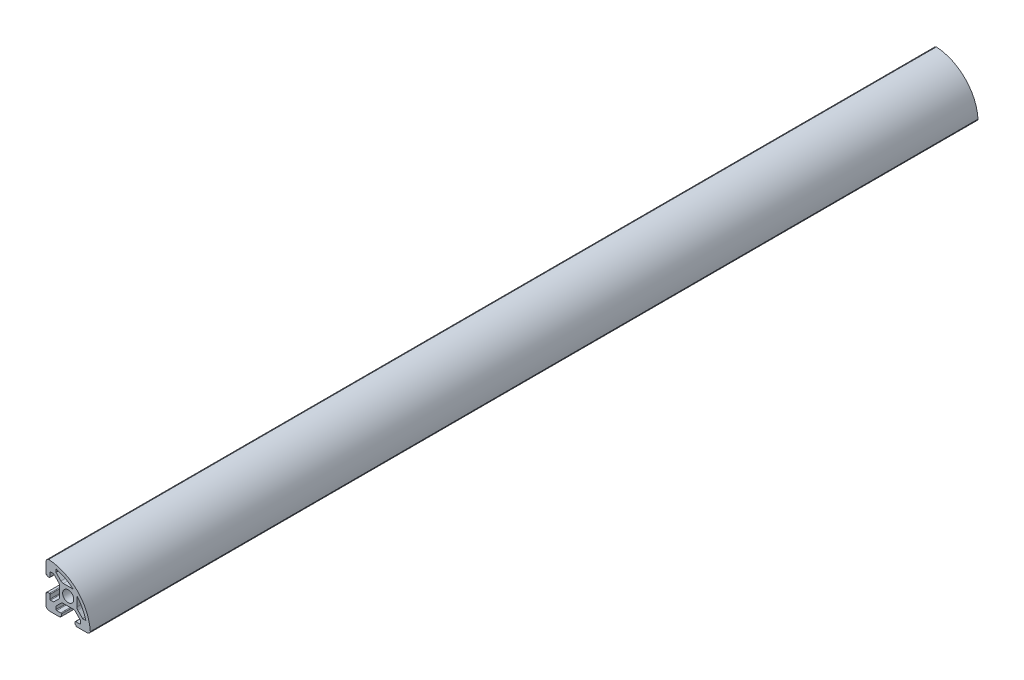
SolidWorks part; units mm, degrees
ref_plane "前视基准面" through (0, 0, 0) normal (0, 0, 1) x (1, 0, 0)
ref_plane "上视基准面" through (0, 0, 0) normal (0, 1, 0) x (1, 0, 0)
ref_plane "右视基准面" through (0, 0, 0) normal (1, 0, 0) x (0, 0, -1)
sketch "草图1" plane through (0, 0, 0) normal (0, 0, 1) x (1, 0, 0)
  line L14 (2.0848, 3.8649) -> (-2.342, 3.8649)
  line L15 (-3.4027, 4.3042) -> (-5.6233, 6.5249)
  line L16 (-5.6233, 6.5249) -> (-5.6233, 7.8649)
  line L22 (-10.1233, 8.4649) -> (-10.1233, 3.5649)
  line L23 (-10.1233, 3.5649) -> (-9.8233, 3.5649)
  line L24 (-9.6233, 3.3649) -> (-9.6233, 3.0649)
  line L25 (-9.6233, 3.0649) -> (-8.6233, 3.0649)
  line L26 (-8.3233, 3.3649) -> (-8.3233, 5.1649)
  line L27 (-8.0233, 5.4649) -> (-6.6833, 5.4649)
  line L28 (-6.6833, 5.4649) -> (-4.4627, 3.2442)
  line L29 (-4.0233, 2.1836) -> (-4.0233, -2.2538)
  line L30 (-4.4627, -3.3144) -> (-6.6833, -5.5351)
  line L31 (-6.6833, -5.5351) -> (-8.0233, -5.5351)
  line L32 (-8.3233, -5.2351) -> (-8.3233, -3.4351)
  line L33 (-8.6233, -3.1351) -> (-9.6233, -3.1351)
  line L34 (-9.6233, -3.1351) -> (-9.6233, -3.4351)
  line L35 (-9.8233, -3.6351) -> (-10.1233, -3.6351)
  line L36 (-10.1233, -3.6351) -> (-10.1233, -8.5351)
  line L37 (-8.6233, -10.0351) -> (-3.7233, -10.0351)
  line L38 (-3.7233, -10.0351) -> (-3.7233, -9.7351)
  line L39 (-3.5233, -9.5351) -> (-3.2233, -9.5351)
  line L40 (-3.2233, -9.5351) -> (-3.2233, -8.5351)
  line L41 (-3.5233, -8.2351) -> (-5.3233, -8.2351)
  line L42 (-5.6233, -7.9351) -> (-5.6233, -6.5951)
  line L43 (-5.6233, -6.5951) -> (-3.4027, -4.3744)
  line L44 (-2.342, -3.9351) -> (2.0953, -3.9351)
  line L45 (3.156, -4.3744) -> (5.3767, -6.5951)
  line L46 (5.3767, -6.5951) -> (5.3767, -7.9351)
  line L47 (5.0767, -8.2351) -> (3.2767, -8.2351)
  line L48 (2.9767, -8.5351) -> (2.9767, -9.5351)
  line L49 (2.9767, -9.5351) -> (3.2767, -9.5351)
  line L50 (3.4767, -9.7351) -> (3.4767, -10.0351)
  line L51 (3.4767, -10.0351) -> (8.3767, -10.0351)
  line L57 (7.7767, -5.5351) -> (6.4367, -5.5351)
  line L58 (6.4367, -5.5351) -> (4.216, -3.3144)
  line L59 (3.7767, -2.2538) -> (3.7767, 2.1836)
  circle A0 centre (-0.1233, -0.0351) radius 2.5
  arc A1 (7.8202, -5.5319) -> (3.7767, 2.1731) centre (-10.1233, -10.0351) ccw
  arc A2 (2.0848, 3.8649) -> (-5.6202, 7.9085) centre (-10.1233, -10.0351) ccw
  arc A9 (-3.4027, 4.3042) -> (-2.342, 3.8649) centre (-2.342, 5.3649) ccw
  arc A10 (-5.3233, 8.1649) -> (-5.6233, 7.8649) centre (-5.3233, 7.8649) ccw
  arc A13 (-8.6233, 9.9649) -> (-10.1233, 8.4649) centre (-8.6233, 8.4649) ccw
  arc A14 (-9.6233, 3.3649) -> (-9.8233, 3.5649) centre (-9.8233, 3.3649) ccw
  arc A15 (-8.6233, 3.0649) -> (-8.3233, 3.3649) centre (-8.6233, 3.3649) ccw
  arc A16 (-8.0233, 5.4649) -> (-8.3233, 5.1649) centre (-8.0233, 5.1649) ccw
  arc A17 (-4.0233, 2.1836) -> (-4.4627, 3.2442) centre (-5.5233, 2.1836) ccw
  arc A18 (-4.4627, -3.3144) -> (-4.0233, -2.2538) centre (-5.5233, -2.2538) ccw
  arc A19 (-8.3233, -5.2351) -> (-8.0233, -5.5351) centre (-8.0233, -5.2351) ccw
  arc A20 (-8.3233, -3.4351) -> (-8.6233, -3.1351) centre (-8.6233, -3.4351) ccw
  arc A21 (-9.8233, -3.6351) -> (-9.6233, -3.4351) centre (-9.8233, -3.4351) ccw
  arc A22 (-10.1233, -8.5351) -> (-8.6233, -10.0351) centre (-8.6233, -8.5351) ccw
  arc A23 (-3.5233, -9.5351) -> (-3.7233, -9.7351) centre (-3.5233, -9.7351) ccw
  arc A24 (-3.2233, -8.5351) -> (-3.5233, -8.2351) centre (-3.5233, -8.5351) ccw
  arc A25 (-5.6233, -7.9351) -> (-5.3233, -8.2351) centre (-5.3233, -7.9351) ccw
  arc A26 (-2.342, -3.9351) -> (-3.4027, -4.3744) centre (-2.342, -5.4351) ccw
  arc A27 (3.156, -4.3744) -> (2.0953, -3.9351) centre (2.0953, -5.4351) ccw
  arc A28 (5.0767, -8.2351) -> (5.3767, -7.9351) centre (5.0767, -7.9351) ccw
  arc A29 (3.2767, -8.2351) -> (2.9767, -8.5351) centre (3.2767, -8.5351) ccw
  arc A30 (3.4767, -9.7351) -> (3.2767, -9.5351) centre (3.2767, -9.7351) ccw
  arc A31 (8.3767, -10.0351) -> (9.8767, -8.5351) centre (8.3767, -8.5351) ccw
  arc A34 (7.7767, -5.5351) -> (7.8202, -5.5319) centre (7.7767, -5.2351) ccw
  arc A35 (3.7767, -2.2538) -> (4.216, -3.3144) centre (5.2767, -2.2538) ccw
  arc A37 (9.8419, -8.8562) -> (-8.9445, 9.9301) centre (-10.1233, -10.0351) ccw
extrude "凸台-拉伸1" add sketch "草图1" along normal blind 400 contours A31 A37 A13 L22 L23 A14 L24 L25 A15 L26 A16 L27 L28 A17 L29 A18 L30 L31 A19 L32 A20 L33 L34 A21 L35 L36 A22 L37 L38 A23 L39 L40 A24 L41 A25 L42 L43 A26 L44 A27 L45 L46 A28 L47 A29 L48 L49 A30 L50 L51
